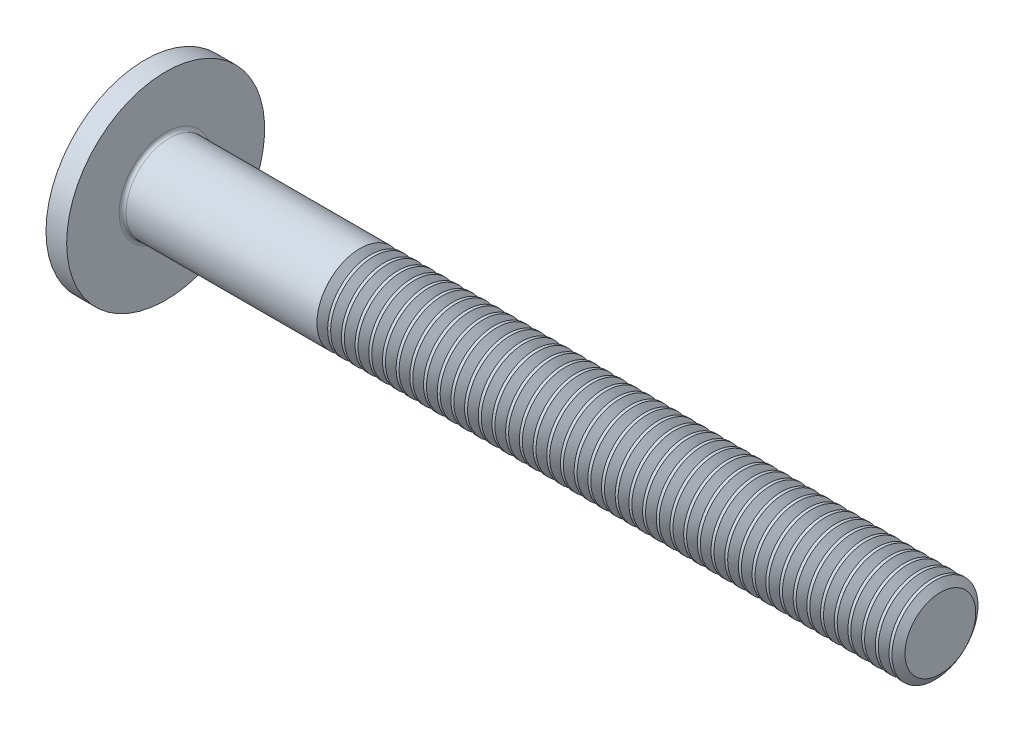
SolidWorks part; units mm, degrees
ref_plane "Plane1" through (0, 0, 0) normal (0, 0, 1) x (1, 0, 0)
ref_plane "Plane2" through (0, 0, 0) normal (0, 1, 0) x (1, 0, 0)
ref_plane "Plane3" through (0, 0, 0) normal (1, 0, 0) x (0, 0, -1)
sketch "BodySke" plane through (0, 0, 0) normal (0, 0, 1) x (1, 0, 0)
  line L1 (3.55, 2.5) -> (3.55, 5.75)
  line L2 (3.55, 2.5) -> (48.55, 2.5)
  line L3 (48.55, 2.5) -> (48.55, 0)
  line L4 (48.55, 0) -> (2.35, 0)
  line L5 (-6.35, 0) -> (82.55, 0) construction
  line L8 (3.55, 5.75) -> (2.35, 5.75)
  line L10 (4.35, 4.0875) -> (4.35, -5.4375) construction
  line L11 (15.15, 4.85) -> (15.15, -4.675) construction
  line L12 (2.35, 5.75) -> (2.35, 0)
  dimension "Diameter" = 5
  dimension "Length" = 45
  dimension "Head_ht" = 3.55
  dimension "Head_dia" = 11.5
  dimension "Advance" = 0.8
  dimension "Thread_nom" = 33.4
  dimension "HTc" = 1.2
revolve "Base-Revolve" add sketch "BodySke"
cosmetic thread "ThreadCosmetic" [suppressed]
revolve "ThreadSchematic" cut sketch "ThdSchSke" angle 360 about L3
sketch "ThdSchSke" plane through (0, 0, 0) normal (0, 0, 1) x (1, 0, 0)
  line L0 (15.15, -2.055) -> (14.8384, -2.5)
  line L1 (15.15, -2.055) -> (15.4616, -2.5)
  line L2 (15.4616, -2.5) -> (15.4616, -3.125)
  line L3 (-3.175, 0) -> (5.1513, 0) construction
  line L4 (3.55, -5.75) -> (3.55, 5.75) construction
  line L5 (15.4616, -3.125) -> (14.8384, -3.125)
  line L6 (14.8384, -3.125) -> (14.8384, -2.5)
  dimension "Thread_minor" = 4.11
  dimension "Diameter" = 5
  dimension "Start" = 11.6
  dimension "SideAngle" = 55
  dimension "VeeAngle" = 70
  dimension "Overcut" = 6.25
fillet "Fillet1" radius 0.2 1 edges at (3.55, 0, 2.5)
sketch "Sketch3" plane through (0, 0, 0) normal (1, 0, 0) x (0, 0, -1)
  line L0 (-0.515, 2.35) -> (0.515, 2.35)
  line L1 (0.515, 2.35) -> (0.515, -2.35)
  line L2 (0.515, -2.35) -> (-0.515, -2.35)
  line L3 (-0.515, -2.35) -> (-0.515, 2.35)
  dimension "D1" = 2.35
  dimension "Cross_dia" = 4.7
  dimension "D2" = 0.515
  dimension "Cross_width" = 1.03
ref_plane "Plane4" through (2.74, 0, 0) normal (1, 0, 0) x (0, 0, -1)
sketch "PanSke" plane through (0, 0, 0) normal (0, 0, 1) x (1, 0, 0)
  line L0 (0, 0) -> (15.875, 0) construction
  line L1 (-6.35, 0) -> (82.55, 0) construction
  line L2 (2.35, 5.75) -> (2.35, -5.75) construction
  line L4 (2.35, 5.0495) -> (2.35, 0)
  line L5 (0, 0) -> (2.35, 0)
  arc A0 (0, 0) -> (2.35, 5.0495) centre (6.6, 0) cw
  dimension "RADf" = 6.6
revolve "Pan" add sketch "PanSke" angle 360 about L0
sketch "Sketch4" plane through (2.74, 0, 0) normal (1, 0, 0) x (0, 0, -1)
  line L0 (-0.515, 2.1065) -> (0.515, 2.1065)
  line L3 (0.515, 2.1065) -> (0.515, -2.1065)
  line L4 (0.515, -2.1065) -> (-0.515, -2.1065)
  line L5 (-0.515, -2.1065) -> (-0.515, 2.1065)
  dimension "D1" = 1.03
  dimension "D2" = 4.213
  dimension "D3" = 0.515
  dimension "D4" = 2.1065
loft "Recess" cut profiles "Sketch3", "Sketch4"
pattern_circular "RecPat" count 2 every 90 about axis through (0, 0, 0) along (1, 0, 0) of "Recess"
sketch "RecCorSke" plane through (0, 0, 0) normal (0, 0, 1) x (1, 0, 0)
  line L0 (-3.175, 0) -> (15.875, 0) construction
  line L2 (0, 0) -> (0, 1.1727)
  line L3 (0, 1.1727) -> (4.6, 0.851)
  line L4 (4.6, 0.851) -> (4.8765, 0)
  line L5 (4.8765, 0) -> (0, 0)
  dimension "Diameter" = 1.702
  dimension "Depth" = 4.6
  dimension "Draft_angle" = 4
  dimension "Bottom_angle" = 18
revolve "RecessCore" cut sketch "RecCorSke" angle 360 about L0
pattern_linear "ThdSchPat" count 43 spacing 0.7952 along (1, 0, 0) of "ThreadSchematic"
equation "\"D1@Sketch3\" = \"Cross_dia@Sketch3\" / 2"
equation "\"D2@Sketch3\" = \"Cross_width@Sketch3\" / 2"
equation "\"D1@Sketch4\" = \"Cross_width@Sketch3\""
equation "\"D3@Sketch4\" = \"D1@Sketch4\" / 2"
equation "\"D4@Sketch4\" = \"D2@Sketch4\" / 2"
equation "\"Thread_length@ThreadCosmetic\" = ((sgn( (\"Length@BodySke\" - \"Advance@BodySke\" * 2.0 ) - \"Thread_nom@BodySke\" )-1)*( (\"Length@BodySke\" - \"Advance@BodySke\" * 2.0 ) - \"Thread_nom@BodySke\" ))/-2+ \"Thread_nom@BodySke\""
equation "\"Thread_minor@ThdSchSke\" = \"Thread_minor@ThreadCosmetic\""
equation "\"Diameter@ThdSchSke\" = \"Diameter@BodySke\""
equation "\"Overcut@ThdSchSke\" = \"Diameter@BodySke\" * 1.25"
equation "\"Start@ThdSchSke\" =  \"Length@BodySke\" -  \"Thread_length@ThreadCosmetic\"  '---Non-countersunk---"
equation "\"Num_threads@ThdSchPat\" = int( \"Thread_length@ThreadCosmetic\" / \"Advance@BodySke\" + 0.999 )  + 1"
equation "\"Advance@ThdSchPat\" = \"Thread_length@ThreadCosmetic\" /  (\"Num_threads@ThdSchPat\" - 1) 'relax it"
